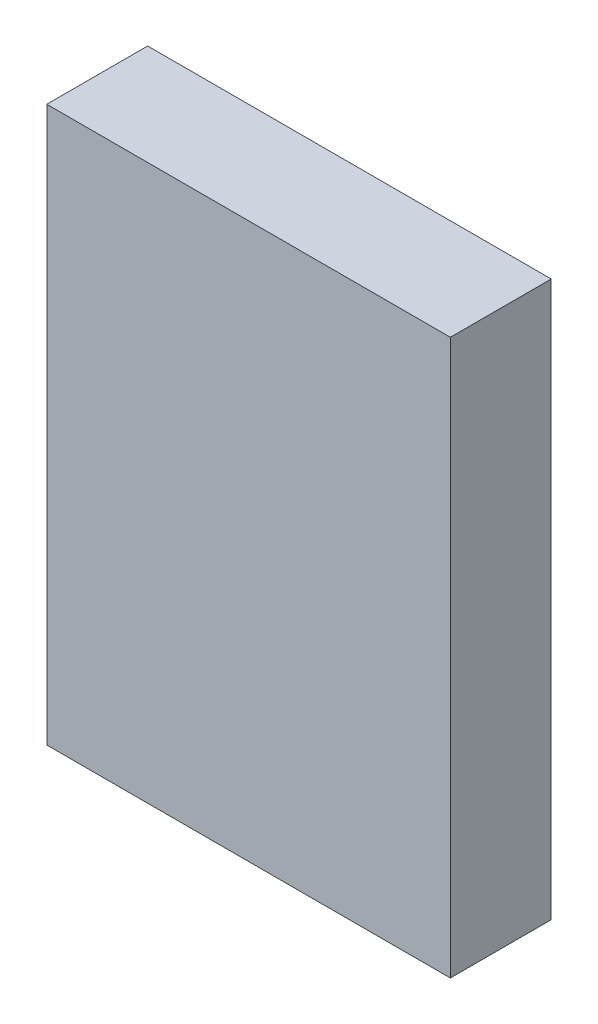
SolidWorks part; units mm, degrees
material "Custom Plastic"
ref_plane "Front Plane" through (0, 0, 0) normal (0, 0, 1) x (1, 0, 0)
ref_plane "Top Plane" through (0, 0, 0) normal (0, 1, 0) x (1, 0, 0)
ref_plane "Right Plane" through (0, 0, 0) normal (1, 0, 0) x (0, 0, -1)
sketch "Sketch1" plane through (0, 0, 0) normal (0, 0, 1) x (1, 0, 0)
  line L1 (-12, -16.5) -> (12, -16.5)
  line L2 (-12, -16.5) -> (-12, 16.5)
  line L3 (-12, 16.5) -> (12, 16.5)
  line L4 (12, -16.5) -> (12, 16.5)
  line L5 (-12, -16.5) -> (12, 16.5) construction
  line L6 (-12, 16.5) -> (12, -16.5) construction
  point P0 (0, 0)
extrude "Boss-Extrude1" add sketch "Sketch1" along normal blind 6
